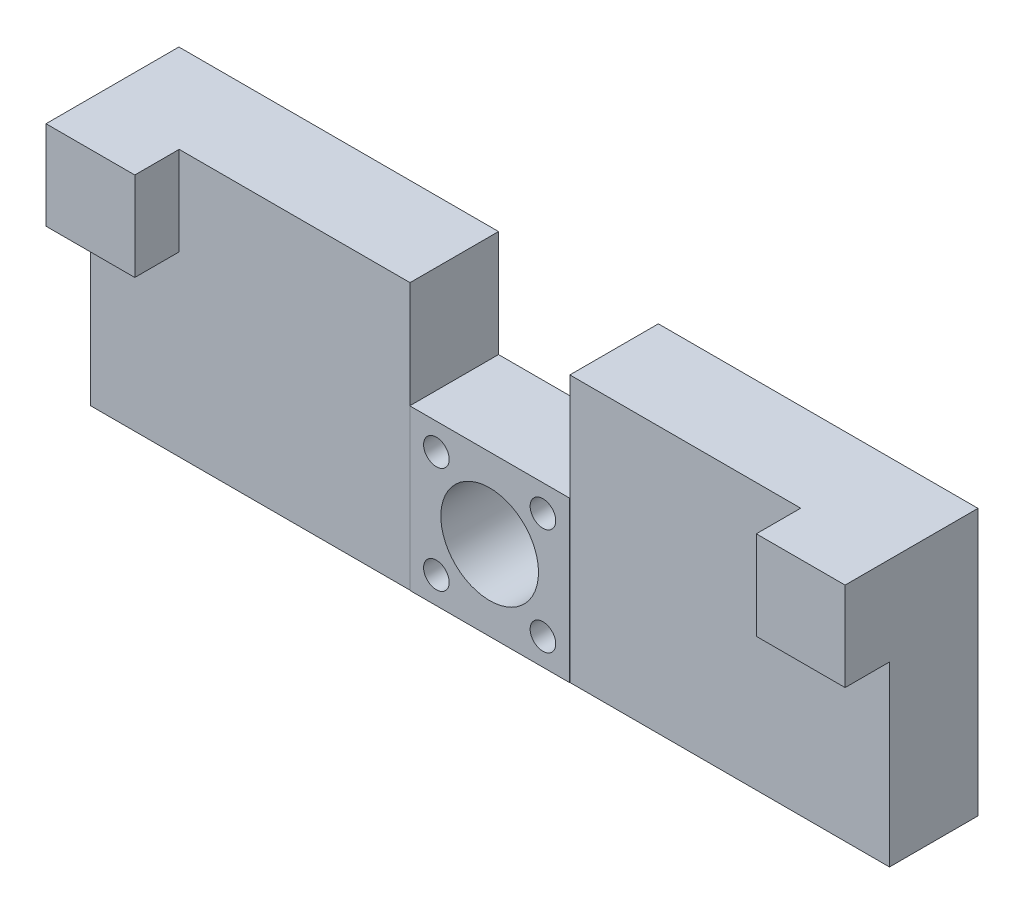
SolidWorks part; units mm, degrees
ref_plane "前视基准面" through (0, 0, 0) normal (0, 0, 1) x (1, 0, 0)
ref_plane "上视基准面" through (0, 0, 0) normal (0, 1, 0) x (1, 0, 0)
ref_plane "右视基准面" through (0, 0, 0) normal (1, 0, 0) x (0, 0, -1)
sketch "草图1" plane through (0, 0, 0) normal (0, 0, 1) x (1, 0, 0)
  line L1 (9, -9) -> (-9, -9)
  line L2 (9, -9) -> (9, 9)
  line L3 (9, 9) -> (-9, 9)
  line L4 (-9, -9) -> (-9, 9)
  line L5 (9, -9) -> (-9, 9) construction
  line L6 (9, 9) -> (-9, -9) construction
  point P0 (0, 0)
  dimension "D1" = 18
  dimension "D2" = 18
extrude "凸台-拉伸1" add sketch "草图1" along normal blind 10
sketch "草图2" plane through (0, 0, 10) normal (0, 0, 1) x (1, 0, 0)
  line L1 (6, -6) -> (-6, -6) construction
  line L2 (6, -6) -> (6, 6) construction
  line L3 (6, 6) -> (-6, 6) construction
  line L4 (-6, -6) -> (-6, 6) construction
  line L5 (6, -6) -> (-6, 6) construction
  line L6 (6, 6) -> (-6, -6) construction
  circle A0 centre (-6, 6) radius 1.4415
  circle A1 centre (6, 6) radius 1.4415
  circle A2 centre (6, -6) radius 1.4415
  circle A3 centre (-6, -6) radius 1.4415
  circle A4 centre (0, 0) radius 5.5
  point P0 (0, 0)
  dimension "D3" = 2.883
  dimension "D4" = 11
  dimension "D1" = 12
  dimension "D2" = 12
extrude "切除-拉伸1" cut sketch "草图2" against normal blind 10
sketch "草图3" plane through (0, -9, 0) normal (0, -1, 0) x (1, 0, 0)
  line L1 (-9, 0) -> (-45, 0)
  line L2 (-9, 0) -> (-9, 9.968)
  line L3 (-9, 9.968) -> (-45, 9.968)
  line L4 (-45, 0) -> (-45, 9.968)
  line L5 (9, 0) -> (45, 0)
  line L6 (9, 0) -> (9, 9.968)
  line L7 (9, 9.968) -> (45, 9.968)
  line L8 (45, 0) -> (45, 9.968)
  dimension "D1" = 36
extrude "凸台-拉伸2" add sketch "草图3" against normal blind 30
sketch "草图4" plane through (0, 0, 9.968) normal (0, 0, 1) x (1, 0, 0)
  line L1 (45, 21) -> (35, 21)
  line L2 (45, 21) -> (45, 11)
  line L3 (45, 11) -> (35, 11)
  line L4 (35, 21) -> (35, 11)
  line L5 (-45, 21) -> (-35, 21)
  line L6 (-45, 21) -> (-45, 11)
  line L7 (-45, 11) -> (-35, 11)
  line L8 (-35, 21) -> (-35, 11)
  dimension "D1" = 10
  dimension "D2" = 10
extrude "凸台-拉伸3" add sketch "草图4" along normal blind 5
